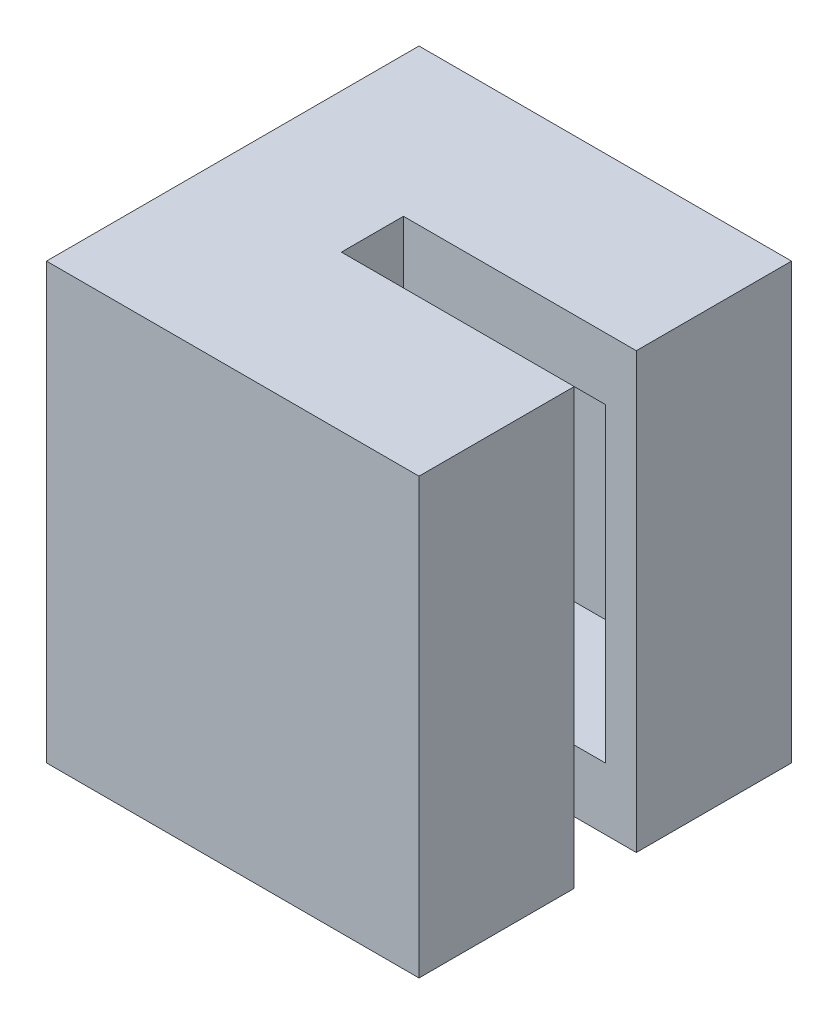
SolidWorks part; units mm, degrees
ref_plane "Front Plane" through (0, 0, 0) normal (0, 0, 1) x (1, 0, 0)
ref_plane "Top Plane" through (0, 0, 0) normal (0, 1, 0) x (1, 0, 0)
ref_plane "Right Plane" through (0, 0, 0) normal (1, 0, 0) x (0, 0, -1)
sketch "Sketch2" plane through (0, 0, 0) normal (0, 1, 0) x (1, 0, 0)
  line L1 (-50, -50) -> (50, -50)
  line L2 (-50, -50) -> (-50, 50)
  line L3 (-50, 50) -> (50, 50)
  line L4 (50, -50) -> (50, 50)
  line L5 (-50, -50) -> (50, 50) construction
  line L6 (-50, 50) -> (50, -50) construction
  line L7 (-60, -60) -> (60, -60)
  line L8 (-60, -60) -> (-60, 60)
  line L9 (-60, 60) -> (60, 60)
  line L10 (60, -60) -> (60, 60)
  line L11 (-60, -60) -> (60, 60) construction
  line L12 (-60, 60) -> (60, -60) construction
  point P0 (0, 0)
  point P6 (0, 0)
  dimension "D1" = 100
  dimension "D2" = 100
  dimension "D3" = 120
extrude "Boss-Extrude1" add sketch "Sketch2" along normal blind 100
sketch "Sketch3" plane through (0, 0, 0) normal (0, -1, 0) x (1, 0, 0)
  line L0 (60, 60) -> (60, -60) construction
  line L1 (-60, -60) -> (60, -60)
  line L2 (-60, -60) -> (-60, 60)
  line L3 (-60, 60) -> (60, 60)
  line L4 (60, -60) -> (60, 60)
  line L5 (-60, -60) -> (60, 60) construction
  line L6 (-60, 60) -> (60, -60) construction
  line L7 (-60, 60) -> (60, 60) construction
  point P0 (0, 0)
extrude "Boss-Extrude2" add sketch "Sketch3" along normal blind 20
sketch "Sketch4" plane through (0, 100, 0) normal (0, 1, 0) x (1, 0, 0)
  line L1 (-60, -60) -> (60, -60)
  line L2 (-60, -60) -> (-60, 60)
  line L3 (-60, 60) -> (60, 60)
  line L4 (60, -60) -> (60, 60)
  line L5 (-60, -60) -> (60, 60) construction
  line L6 (-60, 60) -> (60, -60) construction
  point P0 (0, 0)
extrude "Boss-Extrude3" add sketch "Sketch4" along normal blind 20
sketch "Sketch5" plane through (0, 120, 0) normal (0, 1, 0) x (1, 0, 0)
  line L0 (-15, -10) -> (-15, 10)
  line L1 (-15, 10) -> (60, 10)
  line L2 (-15, -10) -> (60, -10)
  line L3 (60, -60) -> (60, 60) construction
  line L4 (60, 10) -> (60, -10)
  dimension "D1" = 75
  dimension "D2" = 20
extrude "Cut-Extrude1" cut sketch "Sketch5" against normal blind 150
